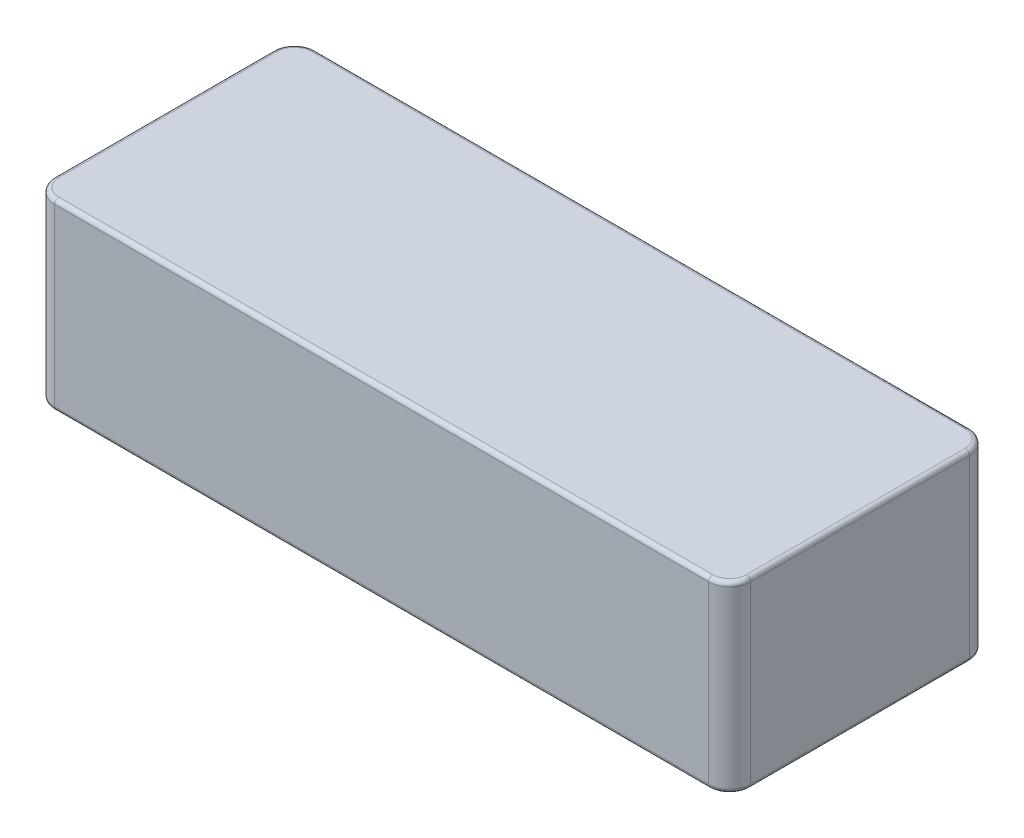
SolidWorks part; units mm, degrees
ref_plane "Front Plane" through (0, 0, 0) normal (0, 0, 1) x (1, 0, 0)
ref_plane "Top Plane" through (0, 0, 0) normal (0, 1, 0) x (1, 0, 0)
ref_plane "Right Plane" through (0, 0, 0) normal (1, 0, 0) x (0, 0, -1)
sketch "Sketch1" plane through (0, 0, 0) normal (0, 1, 0) x (1, 0, 0)
  line L1 (-83, -31.1) -> (83, -31.1)
  line L2 (-83, -31.1) -> (-83, 31.1)
  line L3 (-83, 31.1) -> (83, 31.1)
  line L4 (83, -31.1) -> (83, 31.1)
  line L5 (-83, -31.1) -> (83, 31.1) construction
  line L6 (-83, 31.1) -> (83, -31.1) construction
  point P0 (0, 0)
  dimension "D1" = 62.2
  dimension "D2" = 166
extrude "Boss-Extrude1" add sketch "Sketch1" along normal blind 43.8
fillet "Fillet1" radius 5 4 edges at (83, 21.9, -31.1) (83, 21.9, 31.1) (-83, 21.9, -31.1) (-83, 21.9, 31.1)
fillet "Fillet2" radius 1 16 edges at (-81.5355, 0, -29.6355) (-83, 0, 0) (-81.5355, 0, 29.6355) (0, 0, 31.1) (81.5355, 0, 29.6355) (83, 0, 0) (81.5355, 0, -29.6355) (0, 0, -31.1) (81.5355, 43.8, 29.6355) (0, 43.8, 31.1) (-81.5355, 43.8, 29.6355) (-83, 43.8, 0) (-81.5355, 43.8, -29.6355) (0, 43.8, -31.1) (81.5355, 43.8, -29.6355) (83, 43.8, 0)
sketch "Sketch2" plane through (0, 0, 31.1) normal (0, 0, 1) x (1, 0, 0)
  line L0 (11.5311, 62.1775) -> (373.5311, 62.1775) construction
